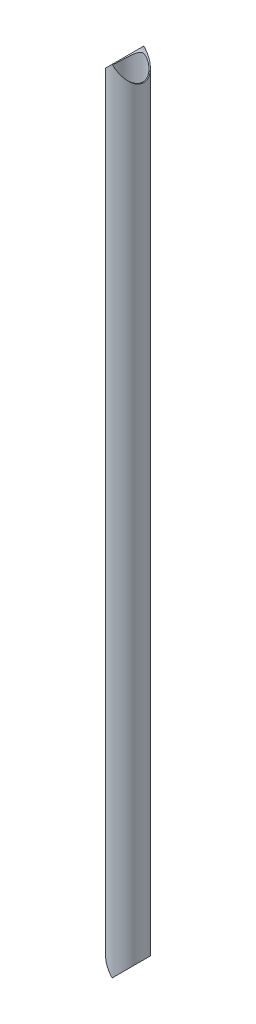
SolidWorks part; units mm, degrees
ref_plane "Plano frontal" through (0, 0, 0) normal (0, 0, 1) x (1, 0, 0)
ref_plane "Plano superior" through (0, 0, 0) normal (0, 1, 0) x (1, 0, 0)
ref_plane "Plano direito" through (0, 0, 0) normal (1, 0, 0) x (0, 0, -1)
sketch "Esboço2" plane through (0, 0, 0) normal (0, 1, 0) x (1, 0, 0)
  circle A0 centre (0, 0) radius 31.75
  circle A1 centre (0, 0) radius 29.75
  dimension "D1" = 63.5
  dimension "D2" = 2
extrude "Ressalto-extrusão1" add sketch "Esboço2" along normal blind 1586.5
sketch "Esboço3" plane through (0, 0, 0) normal (1, 0, 0) x (0, 0, -1)
  circle A0 centre (0, 1586.5) radius 31.75
  circle A1 centre (0, 0) radius 31.75
  point P7 (0, 0)
  dimension "D1" = 1586.5
  dimension "D4" = 63.5
  dimension "D5" = 63.5
extrude "Corte-extrusão1" cut sketch "Esboço3" against normal through all both and the other way through all contours A1 | A0
